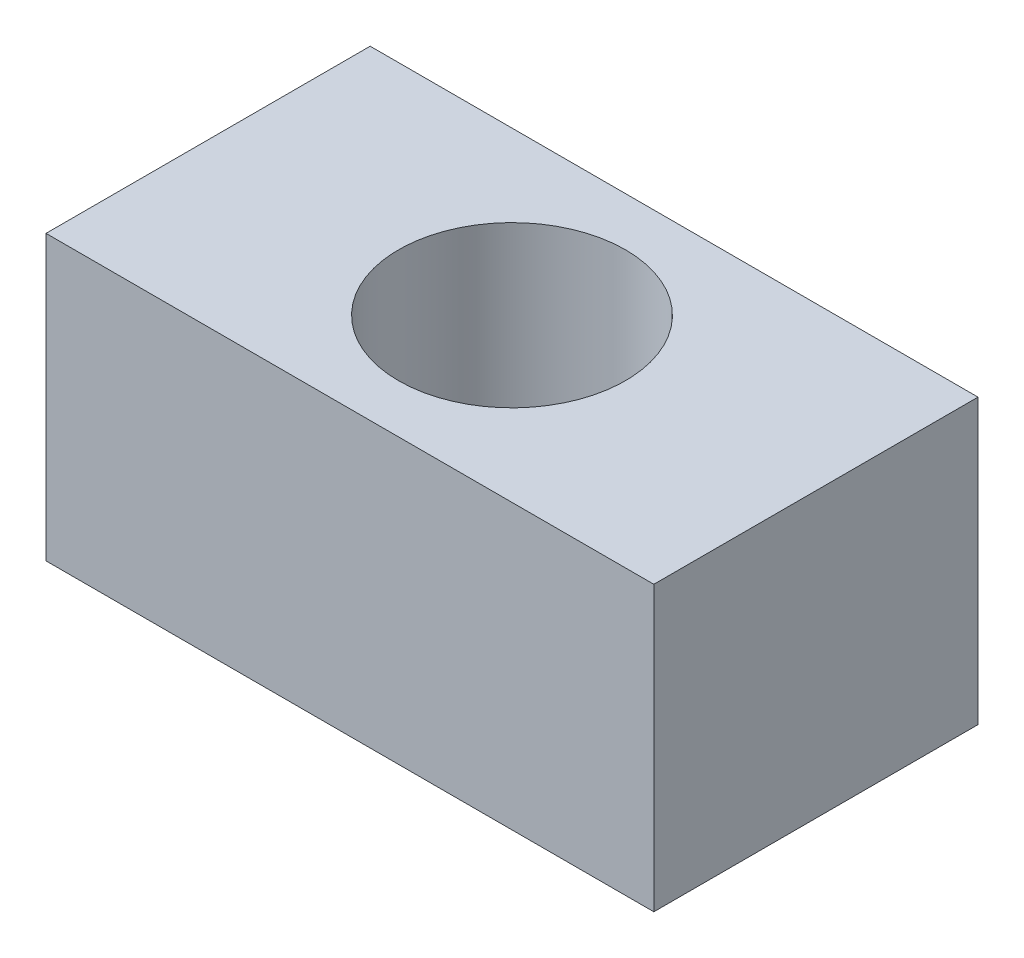
SolidWorks part; units mm, degrees
material "PETG"
ref_plane "Front Plane" through (0, 0, 0) normal (0, 0, 1) x (1, 0, 0)
ref_plane "Top Plane" through (0, 0, 0) normal (0, 1, 0) x (1, 0, 0)
ref_plane "Right Plane" through (0, 0, 0) normal (1, 0, 0) x (0, 0, -1)
sketch "Sketch1" plane through (0, 0, 0) normal (0, 1, 0) x (1, 0, 0)
  line L1 (-53.2999, -24.3333) -> (21.7001, -24.3333)
  line L2 (-53.2999, -24.3333) -> (-53.2999, -64.3333)
  line L3 (-53.2999, -64.3333) -> (21.7001, -64.3333)
  line L4 (21.7001, -24.3333) -> (21.7001, -64.3333)
extrude "Boss-Extrude2" add sketch "Sketch1" along normal blind 35 contours L1 L4 L3 L2
sketch "Sketch2" plane through (0, 0, 0) normal (0, 1, 0) x (1, 0, 0)
  line L2 (-17.4589, -13.8507) -> (-8.8391, -7.5654)
  circle A0 centre (-15.7999, -44.3333) radius 14
extrude "Cut-Extrude3" cut sketch "Sketch2" along normal blind 35 contours A0
